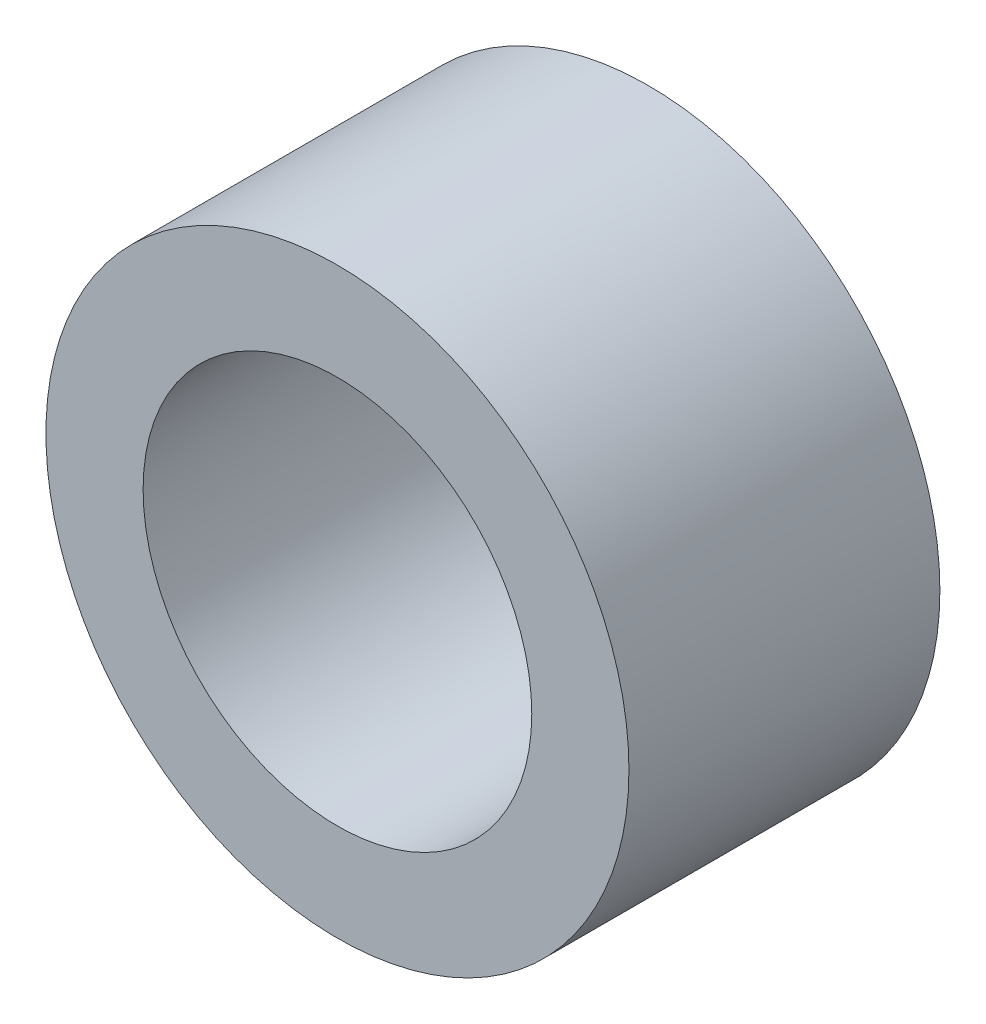
SolidWorks part; units mm, degrees
ref_plane "Front Plane" through (0, 0, 0) normal (0, 0, 1) x (1, 0, 0)
ref_plane "Top Plane" through (0, 0, 0) normal (0, 1, 0) x (1, 0, 0)
ref_plane "Right Plane" through (0, 0, 0) normal (1, 0, 0) x (0, 0, -1)
sketch "Sketch1" plane through (0, 0, 0) normal (0, 0, 1) x (1, 0, 0)
  circle A0 centre (0, 0) radius 7.5
  circle A1 centre (0, 0) radius 5
  dimension "D1" = 10
  dimension "D2" = 15
extrude "Boss-Extrude1" add sketch "Sketch1" along normal blind 8
